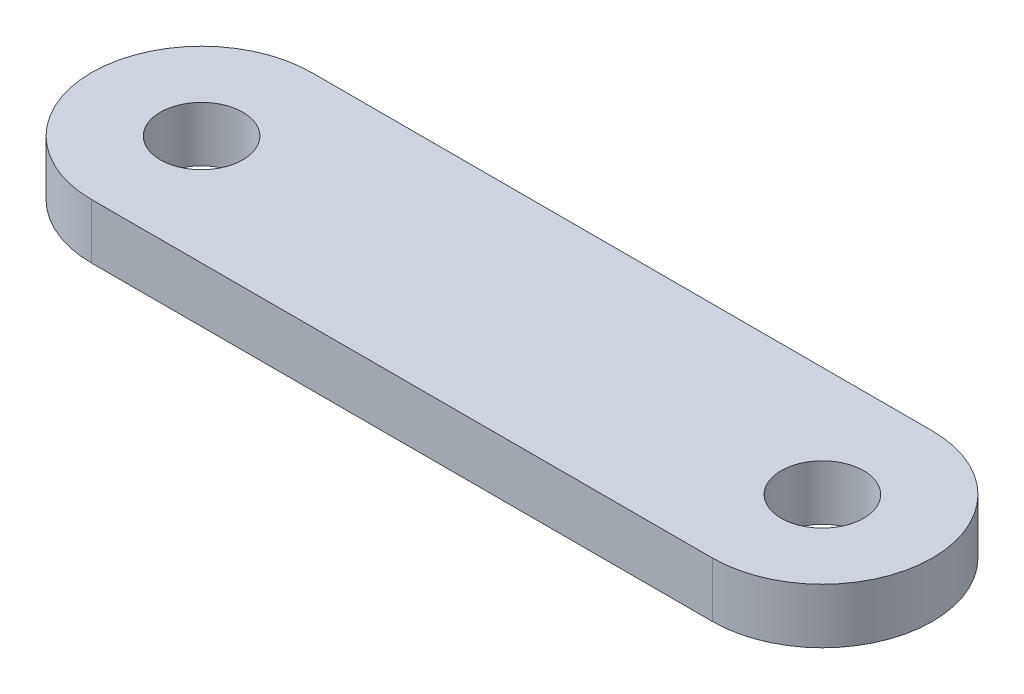
SolidWorks part; units mm, degrees
ref_plane "Front Plane" through (0, 0, 0) normal (0, 0, 1) x (1, 0, 0)
ref_plane "Top Plane" through (0, 0, 0) normal (0, 1, 0) x (1, 0, 0)
ref_plane "Right Plane" through (0, 0, 0) normal (1, 0, 0) x (0, 0, -1)
sketch "Sketch1" plane through (0, 0, 0) normal (0, 1, 0) x (1, 0, 0)
  line L0 (-14.3319, 0) -> (14.3319, 0) construction
  line L1 (-14.3319, 5.08) -> (14.3319, 5.08)
  line L2 (-14.3319, -5.08) -> (14.332, -5.08)
  arc A0 (-14.3319, 5.08) -> (-14.3319, -5.08) centre (-14.3319, 0) ccw
  arc A1 (14.332, -5.08) -> (14.3319, 5.08) centre (14.3319, 0) ccw
  circle A2 centre (-14.3319, 0) radius 1.905
  circle A3 centre (14.3319, 0) radius 1.905
  point P2 (0, 0)
  dimension "D2" = 3.81
  dimension "D3" = 3.175
  dimension "D1" = 28.6639
extrude "Boss-Extrude1" add sketch "Sketch1" along normal blind 2.54
